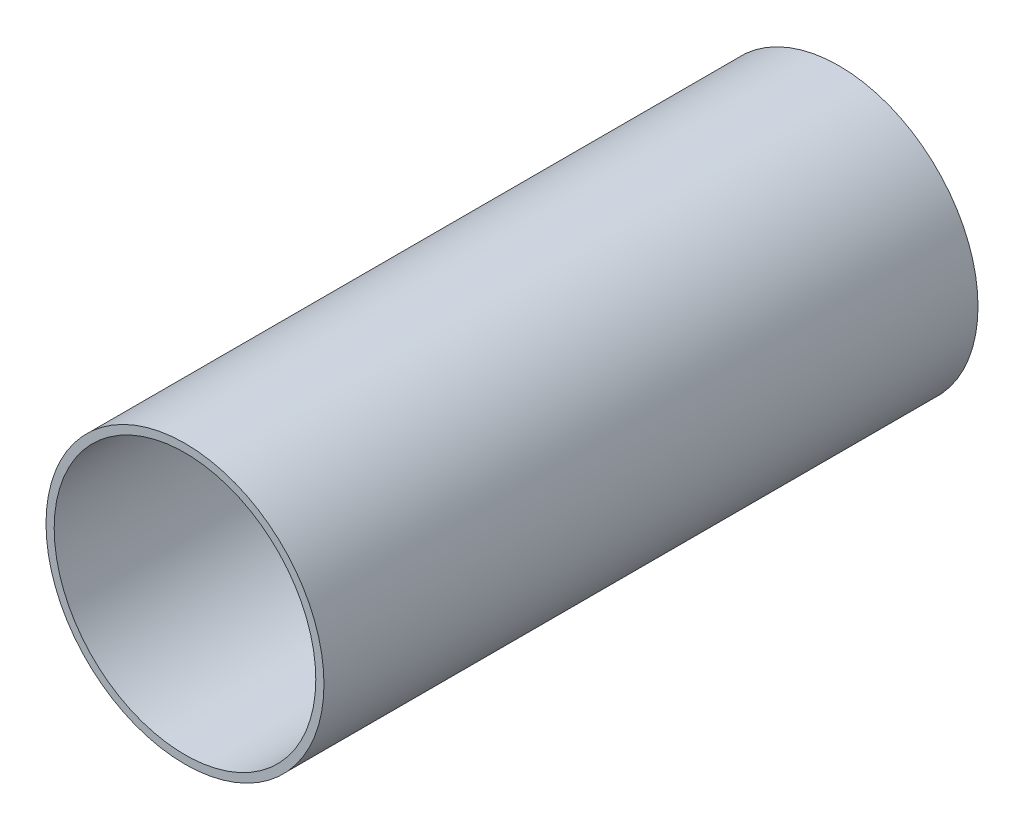
SolidWorks part; units mm, degrees
ref_plane "Front" through (0, 0, 0) normal (0, 0, 1) x (1, 0, 0)
ref_plane "Top" through (0, 0, 0) normal (0, 1, 0) x (1, 0, 0)
ref_plane "Right" through (0, 0, 0) normal (1, 0, 0) x (0, 0, -1)
sketch "Sketch1" plane through (0, 0, 0) normal (1, 0, 0) x (0, 0, -1)
  line L0 (0, 0) -> (6.6, 0) construction
  line L1 (0, 4.25) -> (20, 4.25)
  line L2 (0, 4.25) -> (0, 4)
  line L3 (0, 4) -> (20, 4)
  line L4 (20, 4.25) -> (20, 4)
  dimension "D1" = 20
  dimension "D2" = 8
  dimension "D3" = 8.5
revolve "Revolve1" add sketch "Sketch1" angle 360 about L0
